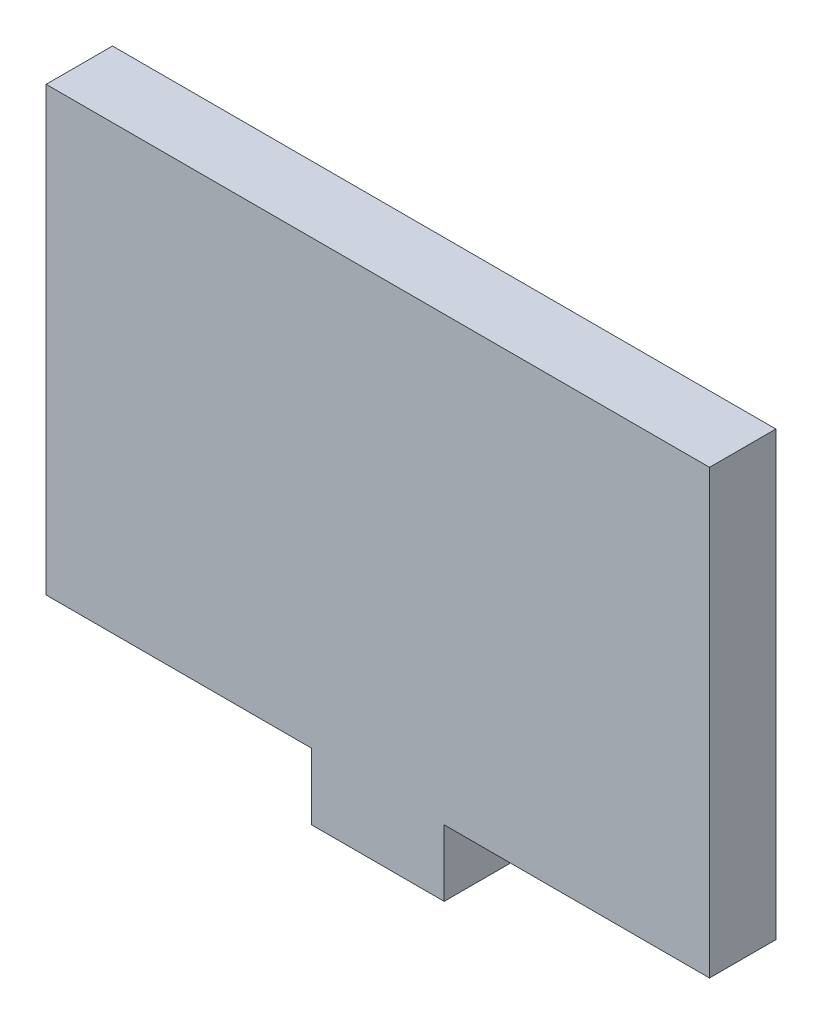
SolidWorks part; units mm, degrees
ref_plane "Front Plane" through (0, 0, 0) normal (0, 0, 1) x (1, 0, 0)
ref_plane "Top Plane" through (0, 0, 0) normal (0, 1, 0) x (1, 0, 0)
ref_plane "Right Plane" through (0, 0, 0) normal (1, 0, 0) x (0, 0, -1)
sketch "Sketch2" plane through (0, 0, 0) normal (0, 0, 1) x (1, 0, 0)
  line L0 (3, -10) -> (15, -10)
  line L1 (-15, 10) -> (15, 10)
  line L2 (-15, 10) -> (-15, -10)
  line L3 (-15, -10) -> (-3, -10)
  line L4 (15, 10) -> (15, -10)
  line L5 (-15, 10) -> (15, -10) construction
  line L6 (-15, -10) -> (15, 10) construction
  line L8 (-3, -10) -> (-3, -13)
  line L9 (-3, -13) -> (3, -13)
  line L10 (3, -10) -> (3, -13)
  line L11 (-3, -7) -> (3, -13) construction
  line L12 (-3, -13) -> (3, -7) construction
  point P0 (0, 0)
  point P6 (0, -10)
  dimension "D1" = 30
  dimension "D2" = 20
  dimension "D3" = 6
  dimension "D4" = 6
extrude "Boss-Extrude1" add sketch "Sketch2" along normal blind 3
